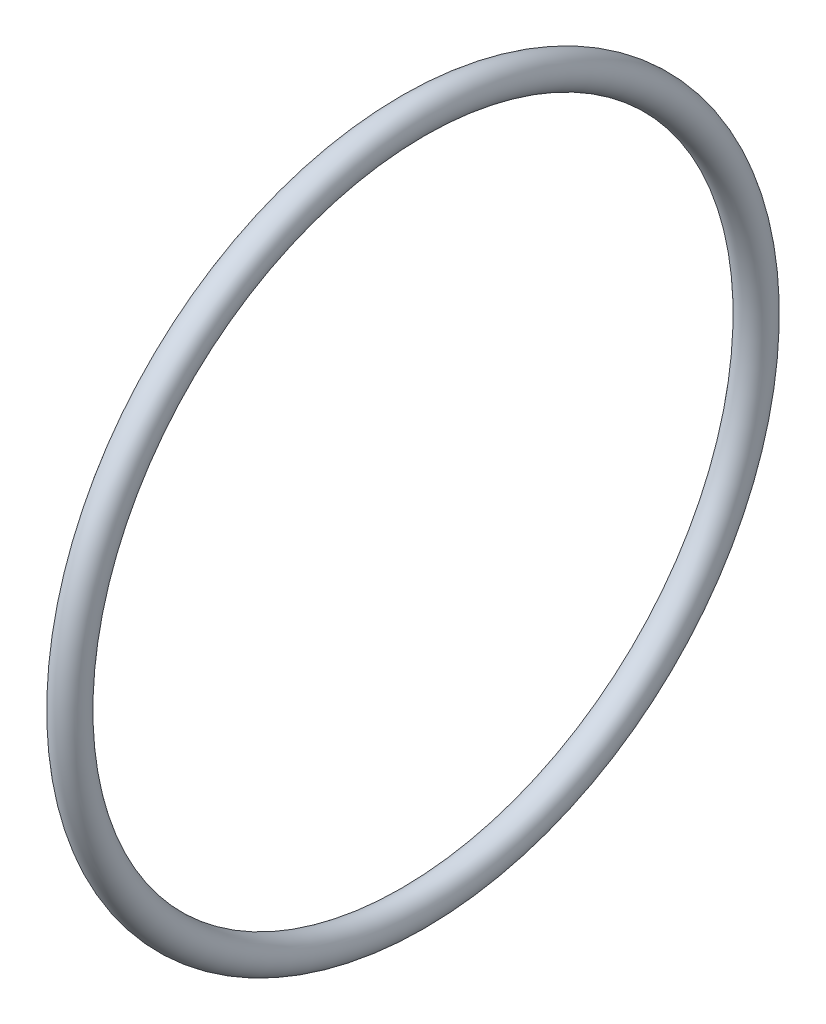
SolidWorks part; units mm, degrees
ref_plane "Front Plane" through (0, 0, 0) normal (0, 0, 1) x (1, 0, 0)
ref_plane "Top Plane" through (0, 0, 0) normal (0, 1, 0) x (1, 0, 0)
ref_plane "Right Plane" through (0, 0, 0) normal (1, 0, 0) x (0, 0, -1)
sketch "Sketch1" plane through (0, 0, 0) normal (1, 0, 0) x (0, 0, -1)
  circle A0 centre (0, 0) radius 21
  dimension "D1" = 42
sketch "Sketch2" plane through (0, 0, 0) normal (0, 0, 1) x (1, 0, 0)
  line L0 (0, -21) -> (0, 21) construction
  circle A0 centre (0, 21) radius 1
  dimension "D1" = 2
sweep "Sweep1" add profiles "Sketch2" path "Sketch1"
move or copy body "Body-Move/Copy1" bodies to move or copy 101
sketch "Sketch3" plane through (0, 0, 0) normal (1, 0, 0) x (0, 0, -1)
  line L0 (0, 0) -> (0, 28.8923) construction
  line L1 (0, 0) -> (28.111, 0) construction
  circle A0 centre (0, 0) radius 10.7426 construction
